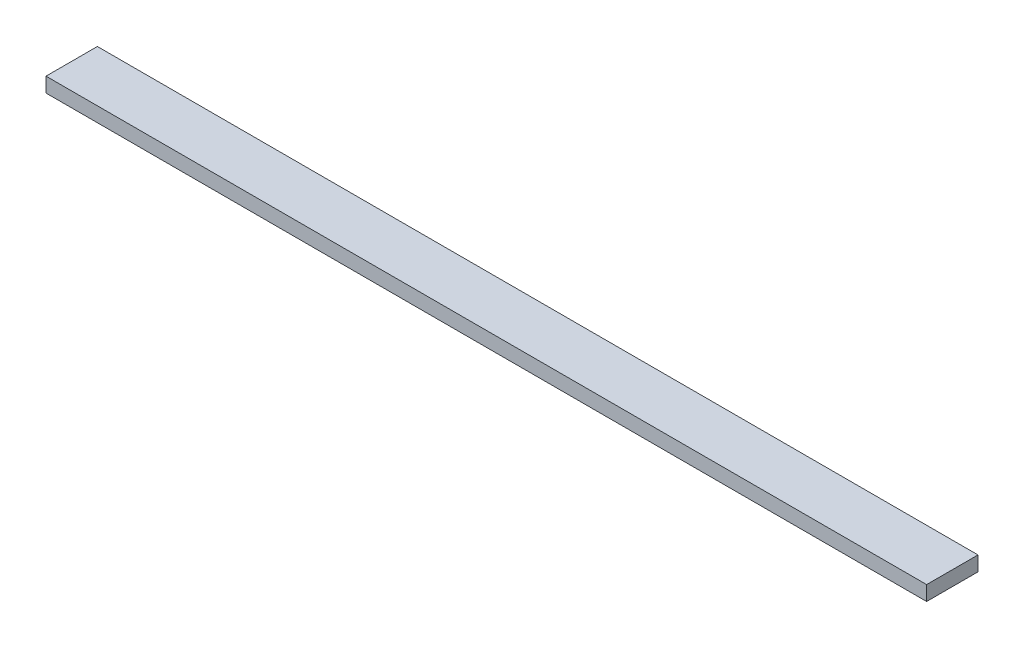
SolidWorks part; units mm, degrees
ref_plane "Front Plane" through (0, 0, 0) normal (0, 0, 1) x (1, 0, 0)
ref_plane "Top Plane" through (0, 0, 0) normal (0, 1, 0) x (1, 0, 0)
ref_plane "Right Plane" through (0, 0, 0) normal (1, 0, 0) x (0, 0, -1)
sketch "Sketch1" plane through (0, 0, 0) normal (0, 1, 0) x (1, 0, 0)
  line L1 (0, 0) -> (600, 0)
  line L2 (0, 0) -> (0, -35)
  line L3 (0, -35) -> (600, -35)
  line L4 (600, 0) -> (600, -35)
  dimension "D1" = 600
  dimension "D2" = 35
extrude "Boss-Extrude1" add sketch "Sketch1" along normal blind 10
